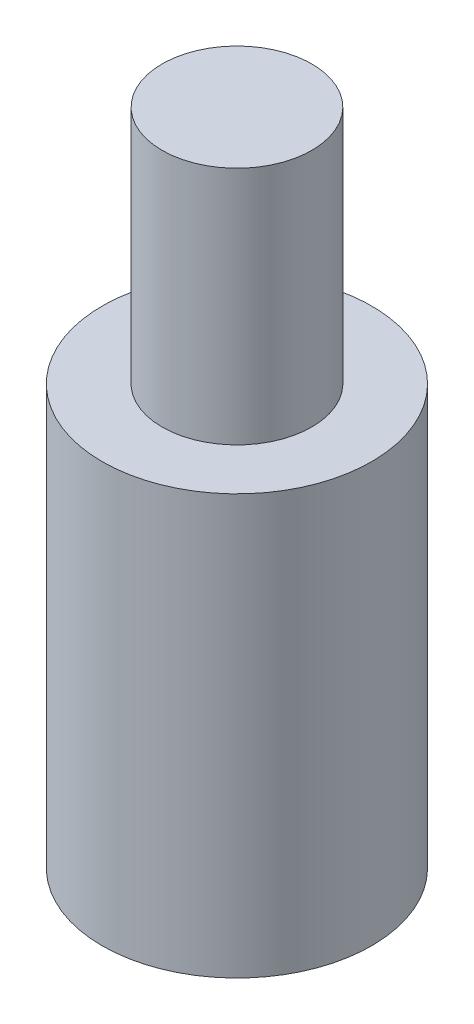
SolidWorks part; units mm, degrees
ref_plane "前视基准面" through (0, 0, 0) normal (0, 0, 1) x (1, 0, 0)
ref_plane "上视基准面" through (0, 0, 0) normal (0, 1, 0) x (1, 0, 0)
ref_plane "右视基准面" through (0, 0, 0) normal (1, 0, 0) x (0, 0, -1)
other "Configuration Table"
sketch "草图1" plane through (0, 0, 0) normal (0, 1, 0) x (1, 0, 0)
  circle A0 centre (0, 0) radius 2.25
  circle A1 centre (0, 0) radius 1.25
  dimension "D1" = 4.5
  dimension "D2" = 2.5
extrude "凸台-拉伸1" add sketch "草图1" along normal blind 7
sketch "草图2" plane through (0, 7, 0) normal (0, 1, 0) x (1, 0, 0)
  circle A0 centre (0, 0) radius 1.25
  dimension "D1" = 2.5
extrude "凸台-拉伸2" add sketch "草图2" along normal blind 4 separate body
